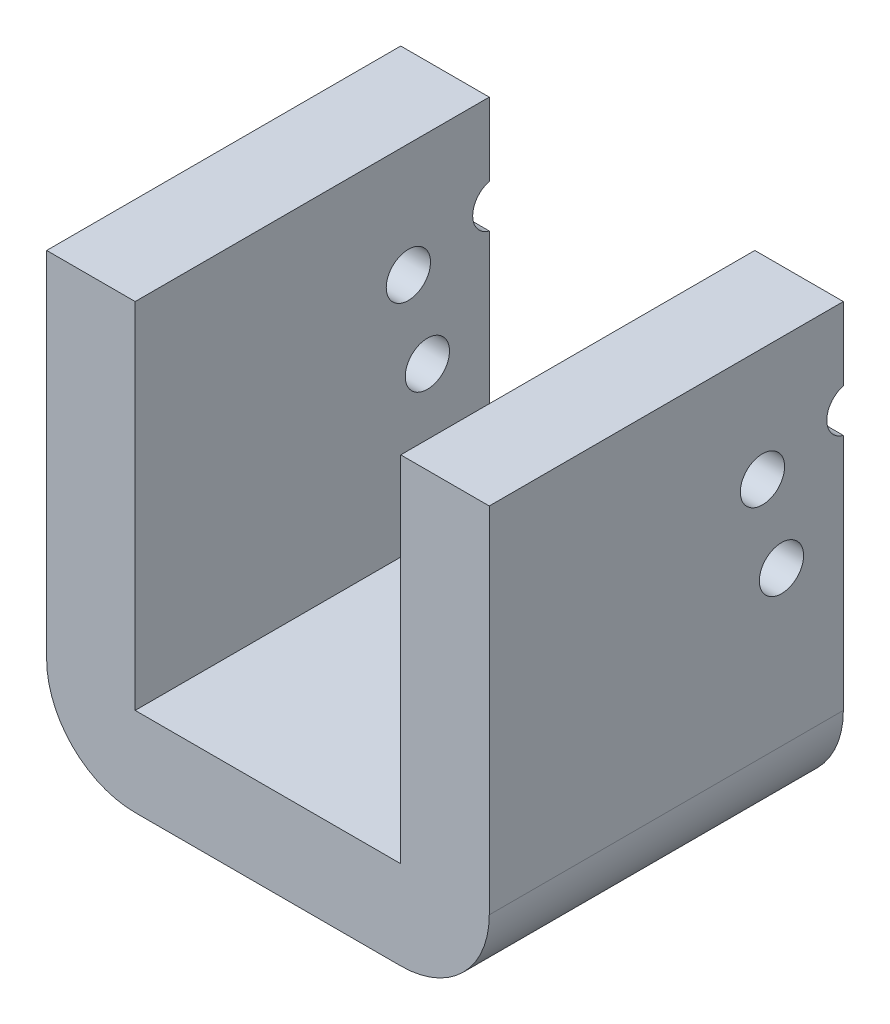
SolidWorks part; units mm, degrees
material "ABS"
ref_plane "Plano frontal" through (0, 0, 0) normal (0, 0, 1) x (1, 0, 0)
ref_plane "Plano superior" through (0, 0, 0) normal (0, 1, 0) x (1, 0, 0)
ref_plane "Plano direito" through (0, 0, 0) normal (1, 0, 0) x (0, 0, -1)
sketch "Esboço1" plane through (0, 0, 0) normal (0, 0, 1) x (1, 0, 0)
  line L0 (0, 0) -> (0, 50)
  line L1 (0, 50) -> (10, 50)
  line L2 (10, 50) -> (10, 10)
  line L3 (10, 10) -> (40, 10)
  line L4 (40, 10) -> (40, 50)
  line L5 (40, 50) -> (50, 50)
  line L6 (50, 50) -> (50, 0)
  line L7 (50, 0) -> (0, 0)
  dimension "D1" = 10
  dimension "D2" = 30
  dimension "D3" = 50
  dimension "D4" = 40
extrude "Ressalto-extrusão1" add sketch "Esboço1" along normal blind 40
sketch "Esboço2" plane through (0, 0, 0) normal (-1, 0, 0) x (0, 0, 1)
  line L0 (20, 50) -> (20, 17.3959) construction
  line L1 (40, 50) -> (0, 50) construction
  circle A1 centre (20, 33.698) radius 5
  dimension "D1" = 10
fillet "Filete1" radius 10 2 edges at (50, 0, 20) (0, 0, 20)
sketch "Esboço3" plane through (0, 0, 0) normal (-1, 0, 0) x (0, 0, 1)
  circle A0 centre (-0.6276, 39.3257) radius 2.5
  circle A1 centre (9.1388, 37.1767) radius 2.5
  circle A2 centre (6.9898, 27.4103) radius 2.5
  circle A3 centre (-2.7766, 29.5593) radius 2.5
extrude "Corte-extrusão1" cut sketch "Esboço3" against normal blind 60
